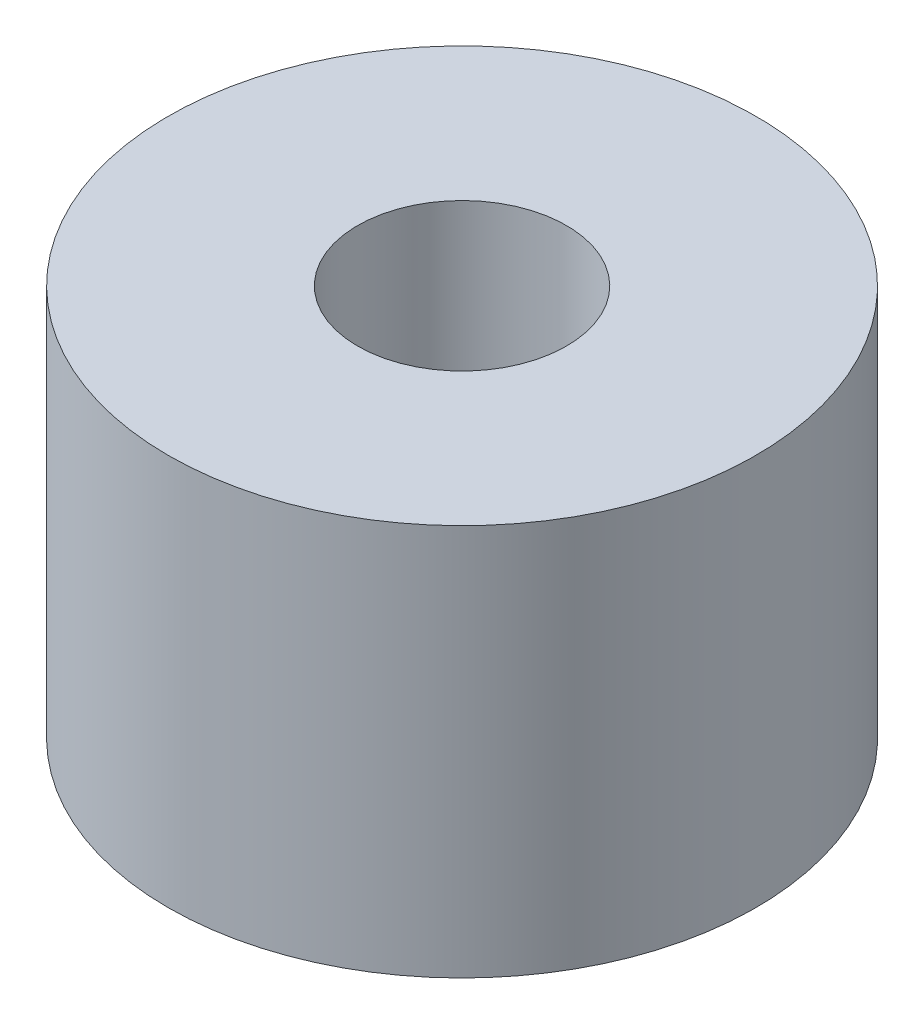
SolidWorks part; units mm, degrees
ref_plane "Front Plane" through (0, 0, 0) normal (0, 0, 1) x (1, 0, 0)
ref_plane "Top Plane" through (0, 0, 0) normal (0, 1, 0) x (1, 0, 0)
ref_plane "Right Plane" through (0, 0, 0) normal (1, 0, 0) x (0, 0, -1)
sketch "Sketch1" plane through (0, 0, 0) normal (0, 1, 0) x (1, 0, 0)
  circle A0 centre (0, 0) radius 2.5
  circle A1 centre (0, 0) radius 11.25
  dimension "D1" = 5
  dimension "D2" = 22.5
extrude "Boss-Extrude1" add sketch "Sketch1" along normal blind 15
sketch "Sketch2" plane through (0, 15, 0) normal (0, 1, 0) x (1, 0, 0)
  circle A0 centre (0, 0) radius 4
  dimension "D1" = 8
extrude "Cut-Extrude1" cut sketch "Sketch2" against normal blind 10
